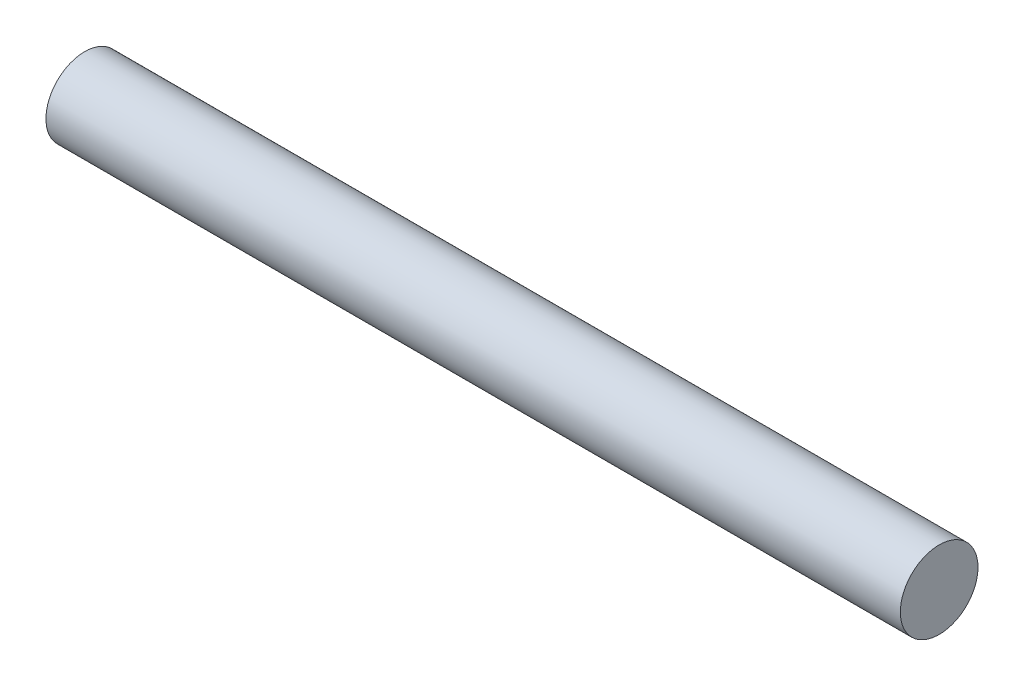
SolidWorks part; units mm, degrees
material "Plain Carbon Steel"
ref_plane "Front Plane" through (0, 0, 0) normal (0, 0, 1) x (1, 0, 0)
ref_plane "Top Plane" through (0, 0, 0) normal (0, 1, 0) x (1, 0, 0)
ref_plane "Right Plane" through (0, 0, 0) normal (1, 0, 0) x (0, 0, -1)
sketch "Sketch1" plane through (0, 0, 0) normal (1, 0, 0) x (0, 0, -1)
  circle A0 centre (0, 0) radius 4
  dimension "D1" = 8
extrude "Boss-Extrude1" add sketch "Sketch1" along normal mid plane 88
ref_plane "Plane1" through (0, 0, 4) normal (0, 0, 1) x (1, 0, 0)
